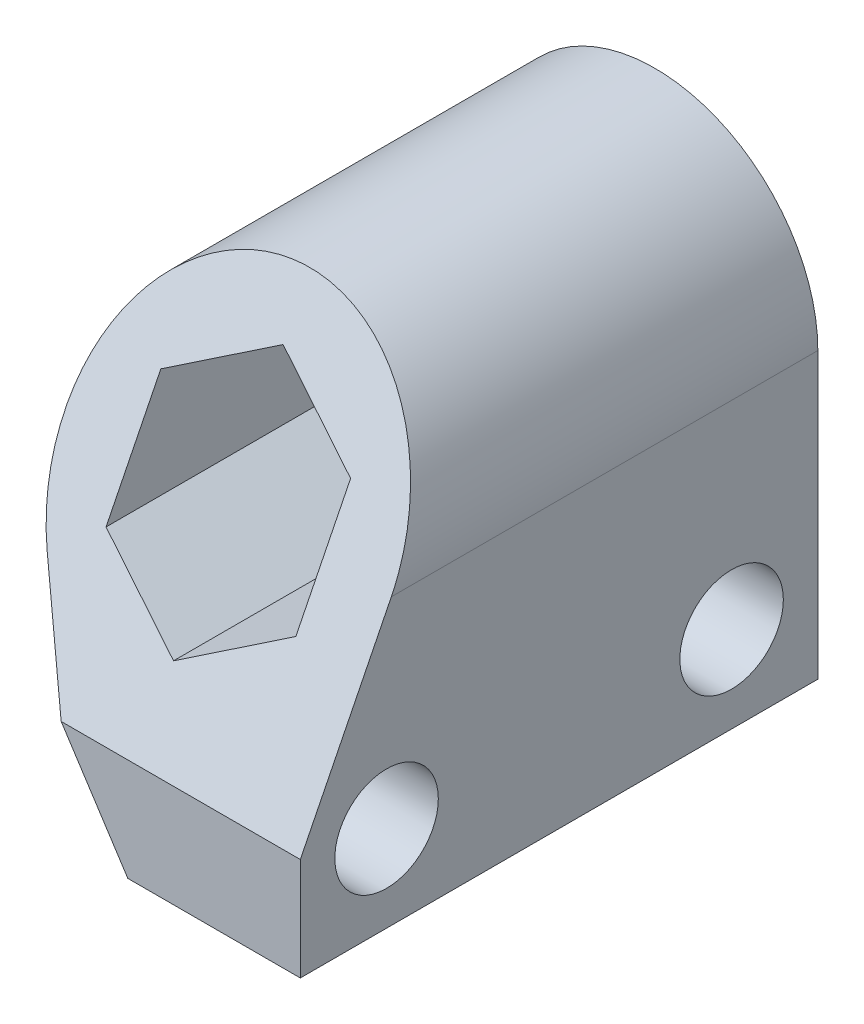
SolidWorks part; units mm, degrees
ref_plane "Front Plane" through (0, 0, 0) normal (0, 0, 1) x (1, 0, 0)
ref_plane "Top Plane" through (0, 0, 0) normal (0, 1, 0) x (1, 0, 0)
ref_plane "Right Plane" through (0, 0, 0) normal (1, 0, 0) x (0, 0, -1)
sketch "Sketch1" plane through (0, 0, 0) normal (0, 0, 1) x (1, 0, 0)
  line L0 (6, 0) -> (6, -10.4775)
  line L1 (3.4925, -2.0164) -> (3.4925, 2.0164)
  line L2 (3.4925, 2.0164) -> (0, 4.0328)
  line L3 (0, 4.0328) -> (-3.4925, 2.0164)
  line L4 (-3.4925, 2.0164) -> (-3.4925, -2.0164)
  line L5 (-3.4925, -2.0164) -> (0, -4.0328)
  line L6 (0, -4.0328) -> (3.4925, -2.0164)
  line L7 (6, -10.4775) -> (-0.35, -10.4775)
  line L8 (-0.35, -10.4775) -> (-5.032, -3.2678)
  line L9 (6, 6.35) -> (6, -29.6307) construction
  circle A0 centre (0, 0) radius 3.4925 construction
  arc A1 (6, 0) -> (-5.032, -3.2678) centre (0, 0) ccw
  dimension "D2" = 6.35
  dimension "D1" = 6.985
  dimension "D3" = 10.4775
extrude "Boss-Extrude1" add sketch "Sketch1" along normal mid plane 19.05
sketch "Sketch2" plane through (6, 0, 0) normal (1, 0, 0) x (0, 0, -1)
  line L0 (-3.175, 6) -> (-9.525, -6.7)
  line L1 (9.525, 6) -> (-9.525, 6) construction
  line L2 (-9.525, -10.4775) -> (-9.525, 0) construction
  line L3 (-9.525, -6.7) -> (-9.525, 6)
  line L4 (-9.525, 6) -> (-3.175, 6)
  dimension "D1" = 6.35
  dimension "D2" = 12.7
extrude "Cut-Extrude1" cut sketch "Sketch2" against normal through all
sketch "Sketch3" plane through (6, 0, 0) normal (1, 0, 0) x (0, 0, -1)
  line L0 (-9.525, -7.3025) -> (-6.35, -7.3025) construction
  line L1 (-9.525, -10.4775) -> (-9.525, -6.7) construction
  line L2 (6.35, -7.3025) -> (9.525, -7.3025) construction
  line L3 (9.525, -10.4775) -> (9.525, 0) construction
  line L4 (-9.525, -10.4775) -> (9.525, -10.4775) construction
  circle A0 centre (-6.35, -7.3025) radius 1.905
  circle A1 centre (6.35, -7.3025) radius 1.905
  dimension "D1" = 3.81
  dimension "D2" = 12.7
  dimension "D3" = 3.175
extrude "Cut-Extrude2" cut sketch "Sketch3" against normal through all
